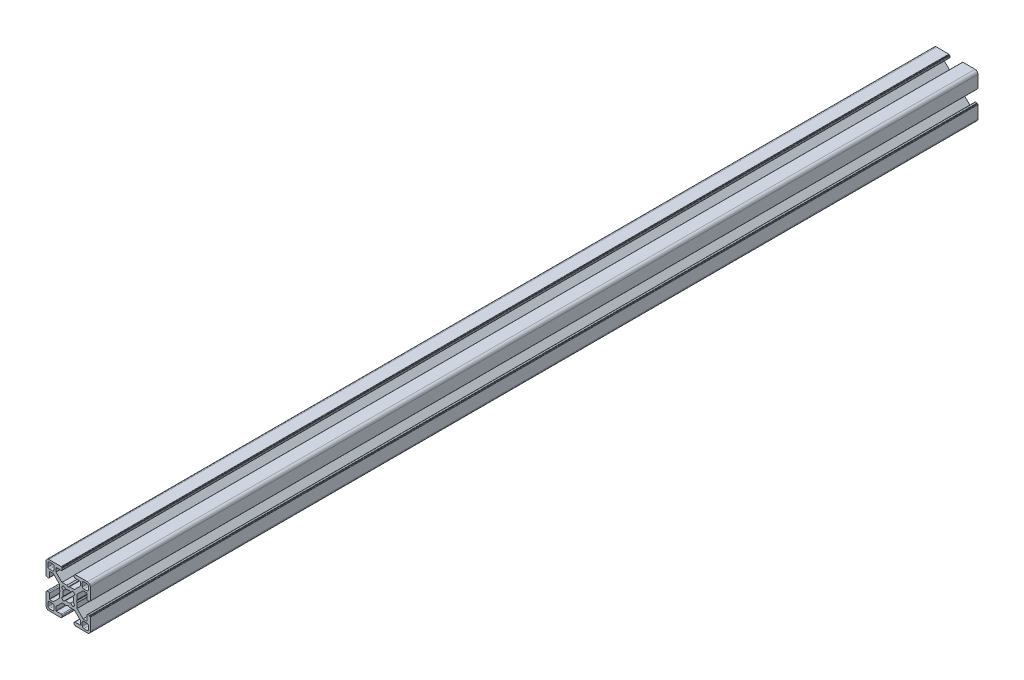
SolidWorks part; units mm, degrees
material "1060 Alloy"
ref_plane "Front" through (0, 0, 0) normal (0, 0, 1) x (1, 0, 0)
ref_plane "Top" through (0, 0, 0) normal (0, 1, 0) x (1, 0, 0)
ref_plane "Right" through (0, 0, 0) normal (1, 0, 0) x (0, 0, -1)
ref_plane "Plane1" through (0, 0, 25) normal (0, 0, 1) x (1, 0, 0)
sketch "Sketch1" plane through (0, 0, 25) normal (0, 0, 1) x (1, 0, 0)
  line L0 (-12.7, 13.7) -> (-10.5, 13.7)
  line L1 (-9.5, 12.7) -> (-9.5, 10.5)
  line L2 (-10.5, 9.5) -> (-12.7, 9.5)
  line L3 (-13.7, 10.5) -> (-13.7, 12.7)
  line L4 (-10.5, -13.7) -> (-12.7, -13.7)
  line L5 (-13.7, -12.7) -> (-13.7, -10.5)
  line L6 (-12.7, -9.5) -> (-10.5, -9.5)
  line L7 (-9.5, -10.5) -> (-9.5, -12.7)
  line L8 (10.5, 13.7) -> (12.7, 13.7)
  line L9 (13.7, 12.7) -> (13.7, 10.5)
  line L10 (12.7, 9.5) -> (10.5, 9.5)
  line L11 (9.5, 10.5) -> (9.5, 12.7)
  line L12 (13.7, -10.5) -> (13.7, -12.7)
  line L13 (12.7, -13.7) -> (10.5, -13.7)
  line L14 (9.5, -12.7) -> (9.5, -10.5)
  line L15 (10.5, -9.5) -> (12.7, -9.5)
  line L16 (-3.1359, 4.5184) -> (-1.6001, 3.2806)
  line L17 (1.6001, 3.2806) -> (3.1359, 4.5184)
  line L18 (4.5053, 3.1547) -> (3.2806, 1.6001)
  line L19 (3.2806, -1.6001) -> (4.5053, -3.1547)
  line L20 (3.1359, -4.5184) -> (1.6001, -3.2806)
  line L21 (-1.6001, -3.2806) -> (-3.1359, -4.5184)
  line L22 (-4.5053, -3.1547) -> (-3.2806, -1.6001)
  line L23 (-3.2806, 1.6001) -> (-4.5053, 3.1547)
  line L24 (-4.05, 13.4) -> (-4.05, 14.3)
  line L25 (-4.25, 14.5) -> (-4.35, 14.5)
  line L26 (-4.55, 14.7) -> (-4.55, 14.8)
  line L27 (-4.75, 15) -> (-13, 15)
  line L28 (-15, 13) -> (-15, 4.75)
  line L29 (-14.8, 4.55) -> (-14.7, 4.55)
  line L30 (-14.5, 4.35) -> (-14.5, 4.25)
  line L31 (-14.3, 4.05) -> (-13.4, 4.05)
  line L32 (-12.8, 4.65) -> (-12.8, 8.05)
  line L33 (-12.6, 8.25) -> (-10.05, 8.25)
  line L34 (-10.05, 8.25) -> (-6.0045, 4.2045)
  line L35 (-6.0045, 4.2045) -> (-6.0045, 0.9)
  line L36 (-6.0045, 0.9) -> (-5.4849, 0)
  line L37 (-5.4849, 0) -> (-6.0045, -0.9)
  line L38 (-6.0045, -0.9) -> (-6.0045, -4.2045)
  line L39 (-6.0045, -4.2045) -> (-10.05, -8.25)
  line L40 (-10.05, -8.25) -> (-12.6, -8.25)
  line L41 (-12.8, -8.05) -> (-12.8, -4.65)
  line L42 (-13.4, -4.05) -> (-14.3, -4.05)
  line L43 (-14.5, -4.25) -> (-14.5, -4.35)
  line L44 (-14.7, -4.55) -> (-14.8, -4.55)
  line L45 (-15, -4.75) -> (-15, -13)
  line L46 (-13, -15) -> (-4.75, -15)
  line L47 (-4.55, -14.8) -> (-4.55, -14.7)
  line L48 (-4.35, -14.5) -> (-4.25, -14.5)
  line L49 (-4.05, -14.3) -> (-4.05, -13.4)
  line L50 (-4.65, -12.8) -> (-8.05, -12.8)
  line L51 (-8.25, -12.6) -> (-8.25, -10.05)
  line L52 (-8.25, -10.05) -> (-4.2045, -6)
  line L53 (-4.2045, -6) -> (-0.9, -6)
  line L54 (-0.9, -6) -> (0, -5.4849)
  line L55 (0, -5.4849) -> (0.9, -6)
  line L56 (0.9, -6) -> (4.2045, -6)
  line L57 (4.2045, -6) -> (8.25, -10.05)
  line L58 (8.25, -10.05) -> (8.25, -12.6)
  line L59 (8.05, -12.8) -> (4.65, -12.8)
  line L60 (4.05, -13.4) -> (4.05, -14.3)
  line L61 (4.25, -14.5) -> (4.35, -14.5)
  line L62 (4.55, -14.7) -> (4.55, -14.8)
  line L63 (4.75, -15) -> (13, -15)
  line L64 (15, -13) -> (15, -4.75)
  line L65 (14.8, -4.55) -> (14.7, -4.55)
  line L66 (14.5, -4.35) -> (14.5, -4.25)
  line L67 (14.3, -4.05) -> (13.4, -4.05)
  line L68 (12.8, -4.65) -> (12.8, -8.05)
  line L69 (12.6, -8.25) -> (10.05, -8.25)
  line L70 (10.05, -8.25) -> (6.0045, -4.2045)
  line L71 (6.0045, -4.2045) -> (6.0045, -0.9)
  line L72 (6.0045, -0.9) -> (5.4849, 0)
  line L73 (5.4849, 0) -> (6.0045, 0.9)
  line L74 (6.0045, 0.9) -> (6.0045, 4.2045)
  line L75 (6.0045, 4.2045) -> (10.05, 8.25)
  line L76 (10.05, 8.25) -> (12.6, 8.25)
  line L77 (12.8, 8.05) -> (12.8, 4.65)
  line L78 (13.4, 4.05) -> (14.3, 4.05)
  line L79 (14.5, 4.25) -> (14.5, 4.35)
  line L80 (14.7, 4.55) -> (14.8, 4.55)
  line L81 (15, 4.75) -> (15, 13)
  line L82 (13, 15) -> (4.75, 15)
  line L83 (4.55, 14.8) -> (4.55, 14.7)
  line L84 (4.35, 14.5) -> (4.25, 14.5)
  line L85 (4.05, 14.3) -> (4.05, 13.4)
  line L86 (4.65, 12.8) -> (8.05, 12.8)
  line L87 (8.25, 12.6) -> (8.25, 10.05)
  line L88 (8.25, 10.05) -> (4.2045, 6)
  line L89 (4.2045, 6) -> (0.9, 6)
  line L90 (0.9, 6) -> (0, 5.4849)
  line L91 (0, 5.4849) -> (-0.9, 6)
  line L92 (-0.9, 6) -> (-4.2045, 6)
  line L93 (-4.2045, 6) -> (-8.25, 10.05)
  line L94 (-8.25, 10.05) -> (-8.25, 12.6)
  line L95 (-8.05, 12.8) -> (-4.65, 12.8)
  arc A0 (-13.7, 12.7) -> (-12.7, 13.7) centre (-12.7, 12.7) cw
  arc A1 (-10.5, 13.7) -> (-9.5, 12.7) centre (-10.5, 12.7) cw
  arc A2 (-9.5, 10.5) -> (-10.5, 9.5) centre (-10.5, 10.5) cw
  arc A3 (-12.7, 9.5) -> (-13.7, 10.5) centre (-12.7, 10.5) cw
  arc A4 (-9.5, -12.7) -> (-10.5, -13.7) centre (-10.5, -12.7) cw
  arc A5 (-12.7, -13.7) -> (-13.7, -12.7) centre (-12.7, -12.7) cw
  arc A6 (-13.7, -10.5) -> (-12.7, -9.5) centre (-12.7, -10.5) cw
  arc A7 (-10.5, -9.5) -> (-9.5, -10.5) centre (-10.5, -10.5) cw
  arc A8 (9.5, 12.7) -> (10.5, 13.7) centre (10.5, 12.7) cw
  arc A9 (12.7, 13.7) -> (13.7, 12.7) centre (12.7, 12.7) cw
  arc A10 (13.7, 10.5) -> (12.7, 9.5) centre (12.7, 10.5) cw
  arc A11 (10.5, 9.5) -> (9.5, 10.5) centre (10.5, 10.5) cw
  arc A12 (13.7, -12.7) -> (12.7, -13.7) centre (12.7, -12.7) cw
  arc A13 (10.5, -13.7) -> (9.5, -12.7) centre (10.5, -12.7) cw
  arc A14 (9.5, -10.5) -> (10.5, -9.5) centre (10.5, -10.5) cw
  arc A15 (12.7, -9.5) -> (13.7, -10.5) centre (12.7, -10.5) cw
  arc A16 (-4.5053, 3.1547) -> (-3.1359, 4.5184) centre (0, 0) cw
  arc A17 (-1.6001, 3.2806) -> (1.6001, 3.2806) centre (0, 0) cw
  arc A18 (3.1359, 4.5184) -> (4.5053, 3.1547) centre (0, 0) cw
  arc A19 (3.2806, 1.6001) -> (3.2806, -1.6001) centre (0, 0) cw
  arc A20 (4.5053, -3.1547) -> (3.1359, -4.5184) centre (0, 0) cw
  arc A21 (1.6001, -3.2806) -> (-1.6001, -3.2806) centre (0, 0) cw
  arc A22 (-3.1359, -4.5184) -> (-4.5053, -3.1547) centre (0, 0) cw
  arc A23 (-3.2806, -1.6001) -> (-3.2806, 1.6001) centre (0, 0) cw
  arc A24 (-4.65, 12.8) -> (-4.05, 13.4) centre (-4.65, 13.4) ccw
  arc A25 (-4.05, 14.3) -> (-4.25, 14.5) centre (-4.25, 14.3) ccw
  arc A26 (-4.35, 14.5) -> (-4.55, 14.7) centre (-4.35, 14.7) cw
  arc A27 (-4.55, 14.8) -> (-4.75, 15) centre (-4.75, 14.8) ccw
  arc A28 (-13, 15) -> (-15, 13) centre (-13, 13) ccw
  arc A29 (-15, 4.75) -> (-14.8, 4.55) centre (-14.8, 4.75) ccw
  arc A30 (-14.7, 4.55) -> (-14.5, 4.35) centre (-14.7, 4.35) cw
  arc A31 (-14.5, 4.25) -> (-14.3, 4.05) centre (-14.3, 4.25) ccw
  arc A32 (-13.4, 4.05) -> (-12.8, 4.65) centre (-13.4, 4.65) ccw
  arc A33 (-12.8, 8.05) -> (-12.6, 8.25) centre (-12.6, 8.05) cw
  arc A34 (-12.6, -8.25) -> (-12.8, -8.05) centre (-12.6, -8.05) cw
  arc A35 (-12.8, -4.65) -> (-13.4, -4.05) centre (-13.4, -4.65) ccw
  arc A36 (-14.3, -4.05) -> (-14.5, -4.25) centre (-14.3, -4.25) ccw
  arc A37 (-14.5, -4.35) -> (-14.7, -4.55) centre (-14.7, -4.35) cw
  arc A38 (-14.8, -4.55) -> (-15, -4.75) centre (-14.8, -4.75) ccw
  arc A39 (-15, -13) -> (-13, -15) centre (-13, -13) ccw
  arc A40 (-4.75, -15) -> (-4.55, -14.8) centre (-4.75, -14.8) ccw
  arc A41 (-4.55, -14.7) -> (-4.35, -14.5) centre (-4.35, -14.7) cw
  arc A42 (-4.25, -14.5) -> (-4.05, -14.3) centre (-4.25, -14.3) ccw
  arc A43 (-4.05, -13.4) -> (-4.65, -12.8) centre (-4.65, -13.4) ccw
  arc A44 (-8.05, -12.8) -> (-8.25, -12.6) centre (-8.05, -12.6) cw
  arc A45 (8.25, -12.6) -> (8.05, -12.8) centre (8.05, -12.6) cw
  arc A46 (4.65, -12.8) -> (4.05, -13.4) centre (4.65, -13.4) ccw
  arc A47 (4.05, -14.3) -> (4.25, -14.5) centre (4.25, -14.3) ccw
  arc A48 (4.35, -14.5) -> (4.55, -14.7) centre (4.35, -14.7) cw
  arc A49 (4.55, -14.8) -> (4.75, -15) centre (4.75, -14.8) ccw
  arc A50 (13, -15) -> (15, -13) centre (13, -13) ccw
  arc A51 (15, -4.75) -> (14.8, -4.55) centre (14.8, -4.75) ccw
  arc A52 (14.7, -4.55) -> (14.5, -4.35) centre (14.7, -4.35) cw
  arc A53 (14.5, -4.25) -> (14.3, -4.05) centre (14.3, -4.25) ccw
  arc A54 (13.4, -4.05) -> (12.8, -4.65) centre (13.4, -4.65) ccw
  arc A55 (12.8, -8.05) -> (12.6, -8.25) centre (12.6, -8.05) cw
  arc A56 (12.6, 8.25) -> (12.8, 8.05) centre (12.6, 8.05) cw
  arc A57 (12.8, 4.65) -> (13.4, 4.05) centre (13.4, 4.65) ccw
  arc A58 (14.3, 4.05) -> (14.5, 4.25) centre (14.3, 4.25) ccw
  arc A59 (14.5, 4.35) -> (14.7, 4.55) centre (14.7, 4.35) cw
  arc A60 (14.8, 4.55) -> (15, 4.75) centre (14.8, 4.75) ccw
  arc A61 (15, 13) -> (13, 15) centre (13, 13) ccw
  arc A62 (4.75, 15) -> (4.55, 14.8) centre (4.75, 14.8) ccw
  arc A63 (4.55, 14.7) -> (4.35, 14.5) centre (4.35, 14.7) cw
  arc A64 (4.25, 14.5) -> (4.05, 14.3) centre (4.25, 14.3) ccw
  arc A65 (4.05, 13.4) -> (4.65, 12.8) centre (4.65, 13.4) ccw
  arc A66 (8.05, 12.8) -> (8.25, 12.6) centre (8.05, 12.6) cw
  arc A67 (-8.25, 12.6) -> (-8.05, 12.8) centre (-8.05, 12.6) cw
extrude "Boss-Extrude1" add sketch "Sketch1" against normal blind 600
